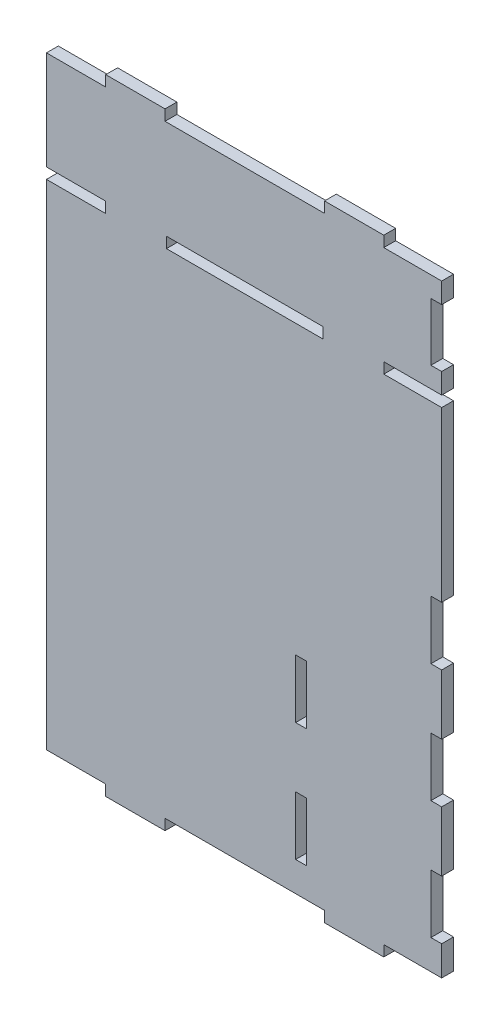
SolidWorks part; units mm, degrees
ref_plane "Спереди" through (0, 0, 0) normal (0, 0, 1) x (1, 0, 0)
ref_plane "Сверху" through (0, 0, 0) normal (0, 1, 0) x (1, 0, 0)
ref_plane "Справа" through (0, 0, 0) normal (1, 0, 0) x (0, 0, -1)
other "Configuration Table"
sketch "Эскиз2" plane through (0, 0, 0) normal (0, 0, 1) x (1, 0, 0)
  line L0 (-99.65, 55.45) -> (-99.65, -250) construction
  line L1 (0, 0) -> (-29.3, 0)
  line L2 (0, 0) -> (0, -85.35)
  line L3 (0, -250) -> (-29.3, -250)
  line L4 (-200, 0) -> (-200, -250)
  line L5 (-170, -250) -> (-200, -250)
  line L7 (-170, -250) -> (-170, -255.45)
  line L8 (-170, -255.45) -> (-140, -255.45)
  line L9 (-140, -250) -> (-140, -255.45)
  line L10 (-29.3, -250) -> (-29.3, -255.45)
  line L11 (-59.3, -250) -> (-59.3, -255.45)
  line L12 (-29.3, -255.45) -> (-59.3, -255.45)
  line L13 (-59.3, -250) -> (-140, -250)
  line L14 (-5.45, -175) -> (0, -175)
  line L15 (-5.45, -235) -> (0, -235)
  line L16 (-5.45, -235) -> (-5.45, -205.35)
  line L17 (-5.45, -205.35) -> (0, -205.35)
  line L19 (-5.45, -175) -> (-5.45, -145.35)
  line L20 (-5.45, -145.35) -> (0, -145.35)
  line L22 (-170, 0) -> (-200, 0)
  line L24 (-170, 0) -> (-170, 5.45)
  line L26 (-139.3, 0) -> (-139.3, 5.45)
  line L27 (-60, 0) -> (-60, 5.45)
  line L29 (-29.3, 0) -> (-29.3, 5.45)
  line L30 (-60, 0) -> (-139.3, 0)
  line L31 (-5.45, -115) -> (0, -115)
  line L32 (-5.45, -115) -> (-5.45, -85.35)
  line L33 (-5.45, -85.35) -> (0, -85.35)
  line L35 (0, -115) -> (0, -145.35)
  line L36 (0, -175) -> (0, -205.35)
  line L37 (0, -235) -> (0, -250)
  line L38 (-68.45, -205.35) -> (-73.9, -205.35)
  line L39 (-68.45, -145.35) -> (-73.9, -145.35)
  line L40 (-68.45, -145.35) -> (-68.45, -175)
  line L41 (-68.45, -175) -> (-73.9, -175)
  line L42 (-73.9, -145.35) -> (-73.9, -175)
  line L43 (-68.45, -205.35) -> (-68.45, -235)
  line L44 (-68.45, -235) -> (-73.9, -235)
  line L45 (-73.9, -205.35) -> (-73.9, -235)
  line L46 (-139.3, 5.45) -> (-60, 5.45)
  line L47 (-200, 5.45) -> (-170, 5.45)
  line L48 (-200, 5.45) -> (-200, 55.45)
  line L49 (-200, 55.45) -> (-170, 55.45)
  line L50 (0, 5.45) -> (0, 15.8)
  line L51 (-29.3, 5.45) -> (0, 5.45)
  line L52 (-29.3, 55.45) -> (0, 55.45)
  line L54 (-29.3, 55.45) -> (-29.3, 60.9)
  line L55 (-29.3, 60.9) -> (-59.3, 60.9)
  line L56 (-59.3, 55.45) -> (-59.3, 60.9)
  line L57 (-170, 55.45) -> (-170, 60.9)
  line L58 (-170, 60.9) -> (-140, 60.9)
  line L59 (-140, 55.45) -> (-140, 60.9)
  line L60 (-140, 55.45) -> (-59.3, 55.45)
  line L61 (0, 30.45) -> (-200, 30.45) construction
  line L62 (0, 15.8) -> (-5.45, 15.8)
  line L64 (0, 45.1) -> (-5.45, 45.1)
  line L65 (-5.45, 15.8) -> (-5.45, 45.1)
  line L66 (0, 45.1) -> (0, 55.45)
  point P49 (-99.65, 55.45)
  point P54 (0, 0)
  dimension "D1" = 200
  dimension "D2" = 250
  dimension "D3" = 30
  dimension "D4" = 5.45
  dimension "D5" = 30
  dimension "D6" = 30.35
  dimension "D7" = 5.45
  dimension "D8" = 29.65
  dimension "D9" = 15
  dimension "D10" = 30.35
  dimension "D11" = 30
  dimension "D12" = 5.45
  dimension "D13" = 29.3
  dimension "D14" = 63
  dimension "D15" = 50
  dimension "D16" = 5.45
  dimension "D17" = 29.3
  dimension "D18" = 29.65
  dimension "D19" = 29.65
  dimension "D20" = 5.45
  dimension "D21" = 30.7
  dimension "D22" = 30
  dimension "D23" = 30
  dimension "D24" = 10.35
  dimension "D25" = 10.35
extrude "Бобышка-Вытянуть1" add sketch "Эскиз2" along normal blind 6
